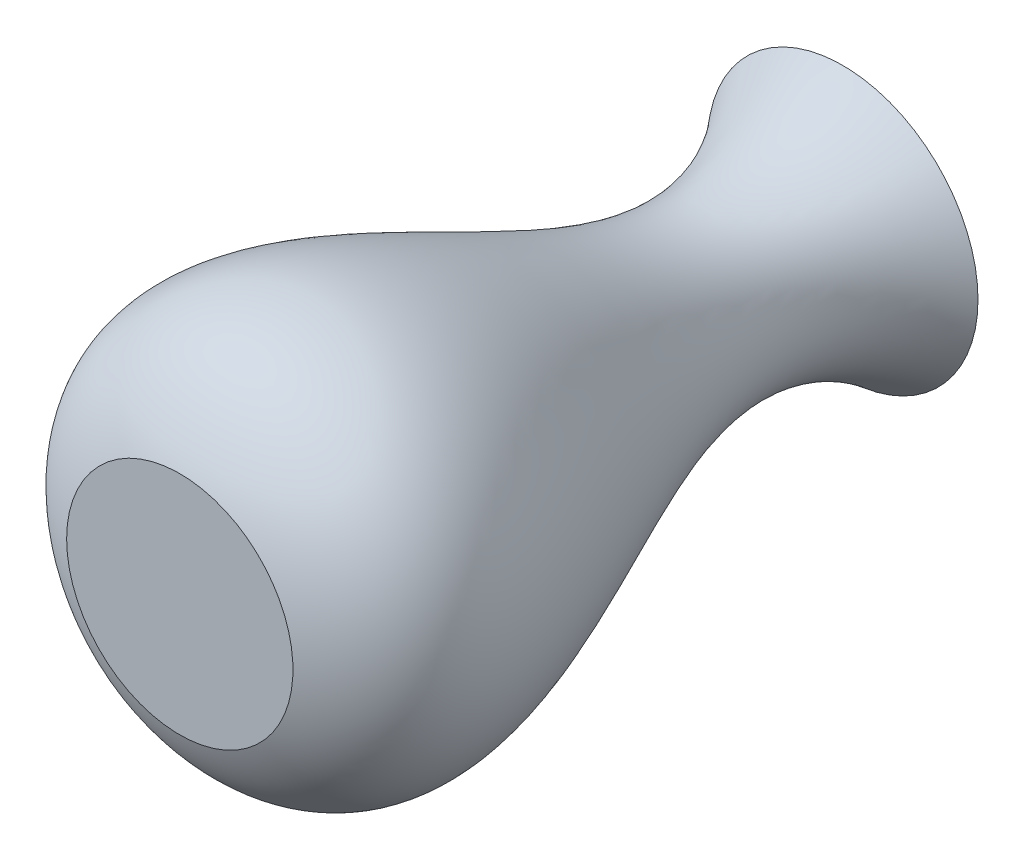
SolidWorks part; units mm, degrees
material "Pure Gold"
ref_plane "Front Plane" through (0, 0, 0) normal (0, 0, 1) x (1, 0, 0)
ref_plane "Top Plane" through (0, 0, 0) normal (0, 1, 0) x (1, 0, 0)
ref_plane "Right Plane" through (0, 0, 0) normal (1, 0, 0) x (0, 0, -1)
sketch "Sketch1" plane through (0, 0, 0) normal (0, 1, 0) x (1, 0, 0)
  line L0 (0, 0) -> (23.9364, 0)
  line L1 (-4.669, 140.2313) -> (23.9364, 140.2313)
  line L2 (23.9364, 140.2313) -> (23.9364, 0)
  spline S0 degree 3 poles (0, 0) (-31.5873, 12.7674) (-4.3055, 72.719) (14.9117, 116.9922) (-4.669, 140.2313) knots 0 0 0 0 0.522405 1 1 1 1
revolve "Revolve1" add sketch "Sketch1" angle 360 about L2
shell "Shell1" thickness 0.254
